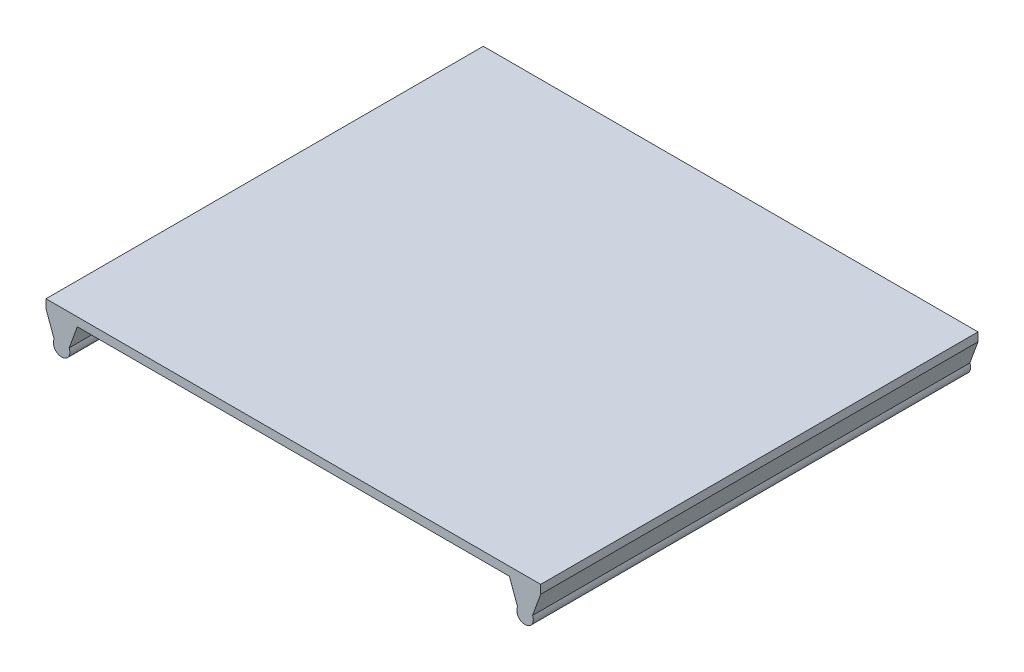
SolidWorks part; units mm, degrees
ref_plane "Front Plane" through (0, 0, 0) normal (0, 0, 1) x (1, 0, 0)
ref_plane "Top Plane" through (0, 0, 0) normal (0, 1, 0) x (1, 0, 0)
ref_plane "Right Plane" through (0, 0, 0) normal (1, 0, 0) x (0, 0, -1)
sketch "Sketch1" plane through (0, 0, 0) normal (0, 0, 1) x (1, 0, 0)
  line L0 (-4.3635, 2) -> (-9.0951, 15)
  line L1 (-9.0951, 15) -> (9.0951, 15)
  line L2 (9.0951, 15) -> (4.3635, 2)
  line L3 (134.5696, -42.8711) -> (134.5696, 84.3152) construction
  line L4 (260.0441, 15) -> (264.7757, 2)
  line L5 (278.2343, 15) -> (260.0441, 15)
  line L6 (273.5027, 2) -> (278.2343, 15)
  line L8 (-9.0951, 15) -> (278.2343, 15)
  line L9 (-9.0951, 15) -> (-9.0951, 20)
  line L10 (-9.0951, 20) -> (278.2343, 20)
  line L11 (278.2343, 15) -> (278.2343, 20)
  circle A0 centre (0, 0) radius 4.8
  circle A1 centre (269.1392, 0) radius 4.8
  dimension "D4" = 9.6
  dimension "D1" = 40
  dimension "D2" = 70
  dimension "D3" = 15
  dimension "D5" = 134.5696
  dimension "D6" = 5
  dimension "D7" = 2
extrude "Boss-Extrude1" add sketch "Sketch1" along normal blind 254 contours L4 A1 L6 L5 | L3 L8 L5 L11 L10 | L8 L3 L10 L9 L1 | A0 L2 L1 L0 | A0 L0
